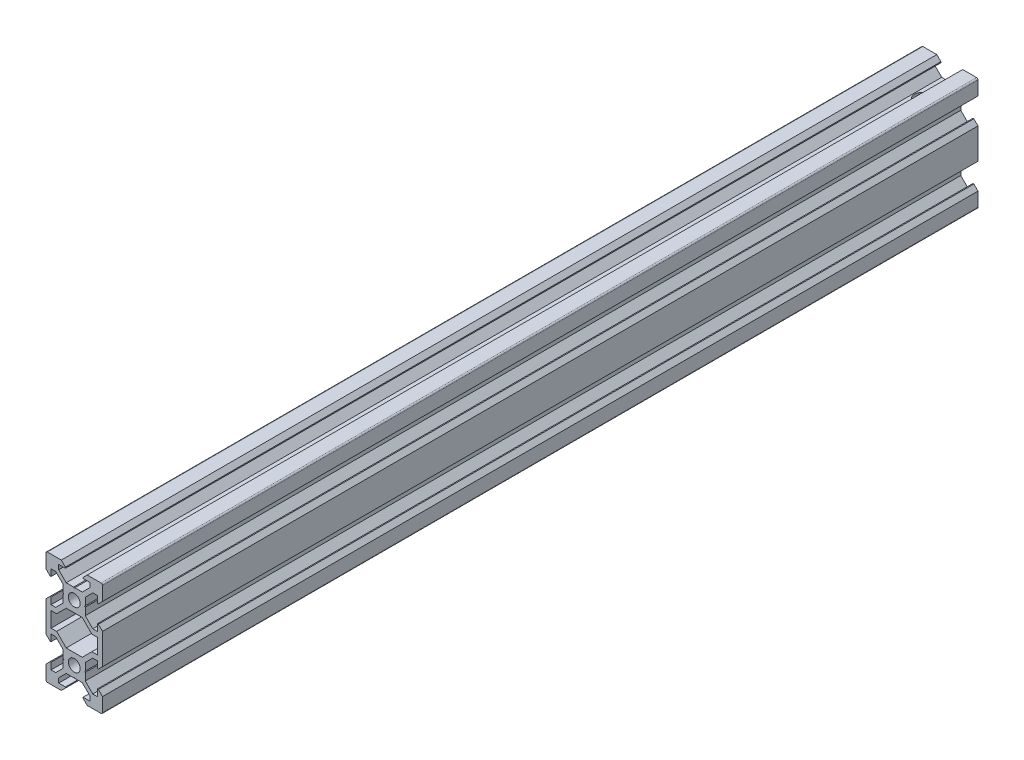
SolidWorks part; units mm, degrees
ref_plane "Plano frontal" through (0, 0, 0) normal (0, 0, 1) x (1, 0, 0)
ref_plane "Plano superior" through (0, 0, 0) normal (0, 1, 0) x (1, 0, 0)
ref_plane "Plano direito" through (0, 0, 0) normal (1, 0, 0) x (0, 0, -1)
sketch "Esboço1" plane through (0, 0, 0) normal (0, 0, 1) x (1, 0, 0)
  line L0 (8.2, -2.7) -> (8.2, 2.7)
  line L1 (8.2, 2.7) -> (6.2393, 2.7)
  line L2 (6.2393, 2.7) -> (2.8393, 6.1)
  line L3 (-2.8393, 6.1) -> (2.8393, 6.1)
  line L4 (-6.2393, 2.7) -> (-2.8393, 6.1)
  line L5 (-8.2, 2.7) -> (-6.2393, 2.7)
  line L6 (-8.2, -2.7) -> (-8.2, 2.7)
  line L7 (-8.2, -2.7) -> (-6.2393, -2.7)
  line L8 (-6.2393, -2.7) -> (-2.8393, -6.1)
  line L9 (-2.8393, -6.1) -> (2.8393, -6.1)
  line L10 (6.2393, -2.7) -> (2.8393, -6.1)
  line L11 (8.2, -2.7) -> (6.2393, -2.7)
  line L12 (3.9, 9.79) -> (3.69, 10)
  line L13 (3.69, 10) -> (3.9, 10.21)
  line L14 (3.9, 10.21) -> (3.9, 12.8393)
  line L15 (3.9, 12.8393) -> (6.5607, 15.5)
  line L16 (6.5607, 15.5) -> (8.2, 15.5)
  line L17 (8.2, 15.5) -> (8.2, 13.125)
  line L18 (8.2, 13.125) -> (8.545, 13.125)
  line L19 (8.545, 13.125) -> (10, 14.58)
  line L20 (10, 14.58) -> (10, 19.5)
  line L21 (9.5, 20) -> (4.58, 20)
  line L22 (4.58, 20) -> (3.125, 18.545)
  line L23 (3.125, 18.545) -> (3.125, 18.2)
  line L24 (3.125, 18.2) -> (5.5, 18.2)
  line L25 (5.5, 18.2) -> (5.5, 16.5607)
  line L26 (5.5, 16.5607) -> (2.8393, 13.9)
  line L27 (2.8393, 13.9) -> (0.21, 13.9)
  line L28 (0.21, 13.9) -> (0, 13.69)
  line L29 (0, 13.69) -> (-0.21, 13.9)
  line L30 (-0.21, 13.9) -> (-2.8393, 13.9)
  line L31 (-2.8393, 13.9) -> (-5.5, 16.5607)
  line L32 (-5.5, 16.5607) -> (-5.5, 18.2)
  line L33 (-5.5, 18.2) -> (-3.125, 18.2)
  line L34 (-3.125, 18.2) -> (-3.125, 18.545)
  line L35 (-3.125, 18.545) -> (-4.58, 20)
  line L36 (-4.58, 20) -> (-9.5, 20)
  line L37 (-10, 19.5) -> (-10, 14.58)
  line L38 (-10, 14.58) -> (-8.545, 13.125)
  line L39 (-8.545, 13.125) -> (-8.2, 13.125)
  line L40 (-8.2, 13.125) -> (-8.2, 15.5)
  line L41 (-8.2, 15.5) -> (-6.5607, 15.5)
  line L42 (-6.5607, 15.5) -> (-3.9, 12.8393)
  line L43 (-3.9, 12.8393) -> (-3.9, 10.21)
  line L44 (-3.9, 10.21) -> (-3.69, 10)
  line L45 (-3.69, 10) -> (-3.9, 9.79)
  line L46 (-3.9, 9.79) -> (-3.9, 7.1607)
  line L47 (-3.9, 7.1607) -> (-6.5607, 4.5)
  line L48 (-6.5607, 4.5) -> (-8.2, 4.5)
  line L49 (-8.2, 4.5) -> (-8.2, 6.875)
  line L50 (-8.2, 6.875) -> (-8.545, 6.875)
  line L51 (-8.545, 6.875) -> (-10, 5.42)
  line L52 (-10, 5.42) -> (-10, -5.42)
  line L53 (-10, -5.42) -> (-8.545, -6.875)
  line L54 (-8.545, -6.875) -> (-8.2, -6.875)
  line L55 (-8.2, -6.875) -> (-8.2, -4.5)
  line L56 (-8.2, -4.5) -> (-6.5607, -4.5)
  line L57 (-6.5607, -4.5) -> (-3.9, -7.1607)
  line L58 (-3.9, -7.1607) -> (-3.9, -9.79)
  line L59 (-3.9, -9.79) -> (-3.69, -10)
  line L60 (-3.69, -10) -> (-3.9, -10.21)
  line L61 (-3.9, -10.21) -> (-3.9, -12.8393)
  line L62 (-3.9, -12.8393) -> (-6.5607, -15.5)
  line L63 (-6.5607, -15.5) -> (-8.2, -15.5)
  line L64 (-8.2, -15.5) -> (-8.2, -13.125)
  line L65 (-8.2, -13.125) -> (-8.545, -13.125)
  line L66 (-8.545, -13.125) -> (-10, -14.58)
  line L67 (-10, -14.58) -> (-10, -19.5)
  line L68 (-9.5, -20) -> (-4.58, -20)
  line L69 (-4.58, -20) -> (-3.125, -18.545)
  line L70 (-3.125, -18.545) -> (-3.125, -18.2)
  line L71 (-3.125, -18.2) -> (-5.5, -18.2)
  line L72 (-5.5, -18.2) -> (-5.5, -16.5607)
  line L73 (-5.5, -16.5607) -> (-2.8393, -13.9)
  line L74 (-2.8393, -13.9) -> (-0.21, -13.9)
  line L75 (-0.21, -13.9) -> (0, -13.69)
  line L76 (0, -13.69) -> (0.21, -13.9)
  line L77 (0.21, -13.9) -> (2.8393, -13.9)
  line L78 (2.8393, -13.9) -> (5.5, -16.5607)
  line L79 (5.5, -16.5607) -> (5.5, -18.2)
  line L80 (5.5, -18.2) -> (3.125, -18.2)
  line L81 (3.125, -18.2) -> (3.125, -18.545)
  line L82 (3.125, -18.545) -> (4.58, -20)
  line L83 (4.58, -20) -> (9.5, -20)
  line L84 (10, -19.5) -> (10, -14.58)
  line L85 (10, -14.58) -> (8.545, -13.125)
  line L86 (8.545, -13.125) -> (8.2, -13.125)
  line L87 (8.2, -13.125) -> (8.2, -15.5)
  line L88 (8.2, -15.5) -> (6.5607, -15.5)
  line L89 (6.5607, -15.5) -> (3.9, -12.8393)
  line L90 (3.9, -12.8393) -> (3.9, -10.21)
  line L91 (3.9, -10.21) -> (3.69, -10)
  line L92 (3.69, -10) -> (3.9, -9.79)
  line L93 (3.9, -9.79) -> (3.9, -7.1607)
  line L94 (3.9, -7.1607) -> (6.5607, -4.5)
  line L95 (6.5607, -4.5) -> (8.2, -4.5)
  line L96 (8.2, -4.5) -> (8.2, -6.875)
  line L97 (8.2, -6.875) -> (8.545, -6.875)
  line L98 (8.545, -6.875) -> (10, -5.42)
  line L99 (10, -5.42) -> (10, 5.42)
  line L100 (10, 5.42) -> (8.545, 6.875)
  line L101 (8.545, 6.875) -> (8.2, 6.875)
  line L102 (8.2, 6.875) -> (8.2, 4.5)
  line L103 (8.2, 4.5) -> (6.5607, 4.5)
  line L104 (6.5607, 4.5) -> (3.9, 7.1607)
  line L105 (3.9, 7.1607) -> (3.9, 9.79)
  circle A0 centre (0, -10) radius 2.1
  circle A1 centre (0, 10) radius 2.1
  arc A2 (10, 19.5) -> (9.5, 20) centre (9.5, 19.5) ccw
  arc A3 (-9.5, 20) -> (-10, 19.5) centre (-9.5, 19.5) ccw
  arc A4 (-10, -19.5) -> (-9.5, -20) centre (-9.5, -19.5) ccw
  arc A5 (9.5, -20) -> (10, -19.5) centre (9.5, -19.5) ccw
extrude "Ressalto-extrusão1" add sketch "Esboço1" along normal blind 310
ref_plane "Plano2" through (0, 0, 0) normal (1, 0, 0) x (0, 0, -1)
ref_plane "Plano3" through (0, 0, 0) normal (0, 1, 0) x (1, 0, 0)
ref_plane "Plano4" through (0, 10, 0) normal (0, 1, 0) x (1, 0, 0)
ref_plane "Plano5" through (0, -10, 0) normal (0, 1, 0) x (1, 0, 0)
sketch "Esboço3" plane through (0, -20, 0) normal (0, -1, 0) x (1, 0, 0)
  circle A0 centre (0, 10) radius 2.1 construction
  circle A1 centre (0, 10) radius 2.1 construction
  circle A2 centre (0, 10) radius 2.5
  dimension "D1" = 5
extrude "Corte-extrusão1" cut sketch "Esboço3" against normal up to surface (40 mm away) up to face at (-7.04, 20, 155)
